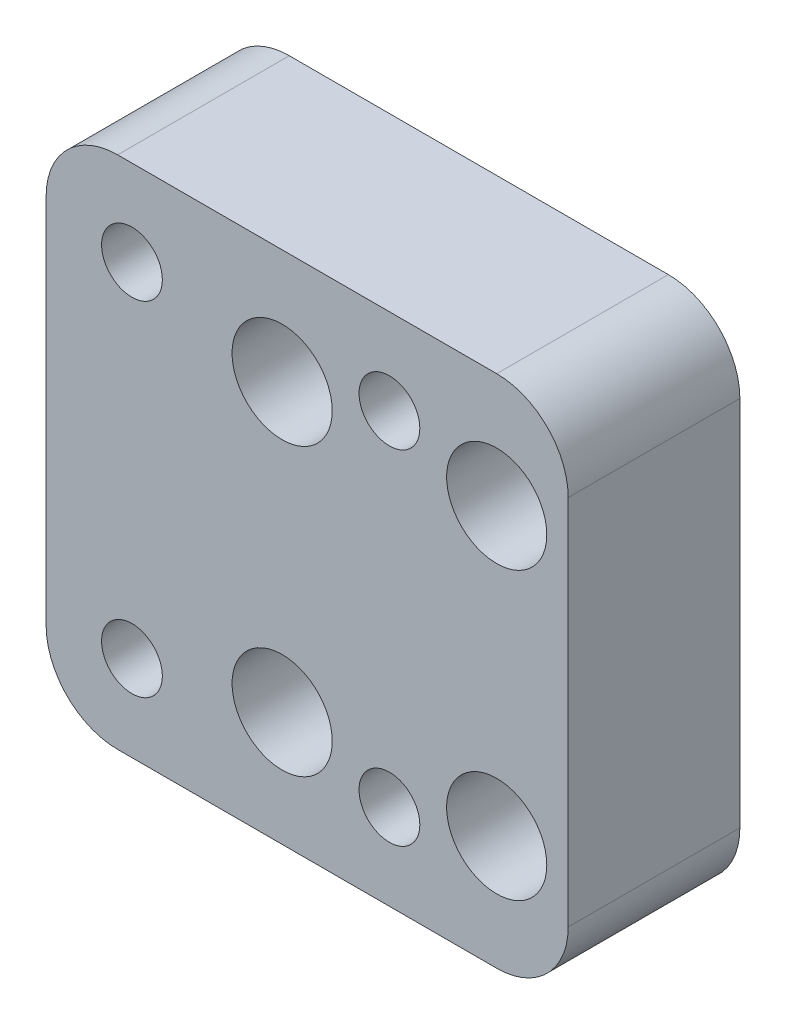
SolidWorks part; units mm, degrees
ref_plane "Front Plane" through (0, 0, 0) normal (0, 0, 1) x (1, 0, 0)
ref_plane "Top Plane" through (0, 0, 0) normal (0, 1, 0) x (1, 0, 0)
ref_plane "Right Plane" through (0, 0, 0) normal (1, 0, 0) x (0, 0, -1)
sketch "Sketch1" plane through (0, 0, 0) normal (0, 0, 1) x (1, 0, 0)
  line L0 (-28.7683, 14.4615) -> (-28.7683, 0) construction
  line L1 (0, 0) -> (15, 0) construction
  line L2 (0, 0) -> (0, 20) construction
  line L3 (0, 20) -> (15, 20) construction
  line L4 (15, 0) -> (15, 20) construction
  line L5 (-28.7683, 0) -> (-25.9188, 0) construction
  line L6 (-25.9188, 0) -> (-25.9188, 5.2985) construction
  line L7 (-25.9188, 5.2985) -> (-20.2199, 5.2985) construction
  line L8 (-20.2199, 5.2985) -> (-20.2199, 7.7568) construction
  line L9 (-20.2199, 7.7568) -> (-25.9188, 7.7568) construction
  line L10 (-25.9188, 7.7568) -> (-25.9188, 12.1707) construction
  line L11 (-25.9188, 12.1707) -> (-20.2199, 12.1707) construction
  line L12 (-20.2199, 12.1707) -> (-20.2199, 14.4615) construction
  line L13 (-20.2199, 14.4615) -> (-28.7683, 14.4615) construction
  line L15 (-10.5, 22) -> (7.5, 22) construction
  line L16 (-10.5, 22) -> (-10.5, -2) construction
  line L17 (-10.5, -2) -> (7.5, -2) construction
  line L18 (7.5, 22) -> (7.5, -2) construction
  line L19 (-16.5, 28) -> (20, 28)
  line L20 (-16.5, 28) -> (-16.5, -8)
  line L21 (-16.5, -8) -> (20, -8)
  line L22 (20, 28) -> (20, -8)
  circle A0 centre (0, 20) radius 1.625
  circle A1 centre (15, 20) radius 1.625
  circle A2 centre (15, 0) radius 1.625
  circle A3 centre (0, 0) radius 1.625
  circle A4 centre (-10.5, 22) radius 2.125
  circle A5 centre (7.5, 22) radius 2.125
  circle A6 centre (7.5, -2) radius 2.125
  circle A7 centre (-10.5, -2) radius 2.125
  point P27 (0, 10)
  point P28 (-10.5, 10)
  point P33 (-16.5, 10)
  dimension "D3" = 3.25
  dimension "D6" = 4.25
  dimension "D1" = 20
  dimension "D2" = 15
  dimension "D4" = 24
  dimension "D5" = 18
  dimension "D7" = 7.5
  dimension "D8" = 6
  dimension "D9" = 5
  dimension "D10" = 6
extrude "Boss-Extrude1" add sketch "Sketch1" along normal blind 12
sketch "Sketch2" plane through (0, 0, 12) normal (0, 0, 1) x (1, 0, 0)
  circle A0 centre (0, 20) radius 3.5
  circle A1 centre (0, 0) radius 3.5
  circle A2 centre (15, 0) radius 3.5
  circle A3 centre (15, 20) radius 3.5
  circle A4 centre (0, 20) radius 1.625 construction
  circle A5 centre (15, 20) radius 1.625 construction
  circle A6 centre (15, 0) radius 1.625 construction
  circle A7 centre (0, 0) radius 1.625 construction
  dimension "D1" = 7
extrude "Cut-Extrude1" cut sketch "Sketch2" against normal offset from surface (8 mm away) 4 up to face at (1.75, 10, 0)
sketch "Sketch3" plane through (0, 0, 0) normal (0, 0, -1) x (-1, 0, 0)
  line L1 (-5.3349, 18.25) -> (-3.1699, 22)
  line L2 (-3.1699, 22) -> (-5.3349, 25.75)
  line L3 (-5.3349, 25.75) -> (-9.6651, 25.75)
  line L4 (-9.6651, 25.75) -> (-11.8301, 22)
  line L5 (-11.8301, 22) -> (-9.6651, 18.25)
  line L6 (-9.6651, 18.25) -> (-5.3349, 18.25)
  line L7 (12.6651, 18.25) -> (14.8301, 22)
  line L8 (14.8301, 22) -> (12.6651, 25.75)
  line L9 (12.6651, 25.75) -> (8.3349, 25.75)
  line L10 (8.3349, 25.75) -> (6.1699, 22)
  line L11 (6.1699, 22) -> (8.3349, 18.25)
  line L12 (8.3349, 18.25) -> (12.6651, 18.25)
  line L13 (12.6651, -5.75) -> (14.8301, -2)
  line L14 (14.8301, -2) -> (12.6651, 1.75)
  line L15 (12.6651, 1.75) -> (8.3349, 1.75)
  line L16 (8.3349, 1.75) -> (6.1699, -2)
  line L17 (6.1699, -2) -> (8.3349, -5.75)
  line L18 (8.3349, -5.75) -> (12.6651, -5.75)
  line L19 (-9.6651, -5.75) -> (-5.3349, -5.75)
  line L20 (-5.3349, -5.75) -> (-3.1699, -2)
  line L21 (-3.1699, -2) -> (-5.3349, 1.75)
  line L22 (-5.3349, 1.75) -> (-9.6651, 1.75)
  line L23 (-9.6651, 1.75) -> (-11.8301, -2)
  line L24 (-11.8301, -2) -> (-9.6651, -5.75)
  circle A0 centre (-7.5, 22) radius 3.75 construction
  circle A1 centre (10.5, 22) radius 3.75 construction
  circle A2 centre (10.5, -2) radius 3.75 construction
  circle A3 centre (-7.5, -2) radius 3.75 construction
  circle A4 centre (-7.5, -2) radius 2.125 construction
  circle A6 centre (-7.5, 22) radius 2.125 construction
  dimension "D1" = 7.5
extrude "Cut-Extrude2" cut sketch "Sketch3" against normal offset from surface (8 mm away) 4 up to face at (18.5, 20, 12)
fillet "Fillet2" radius 5 4 edges at (-16.5, 28, 6) (-16.5, -8, 6) (20, 28, 6) (20, -8, 6)
